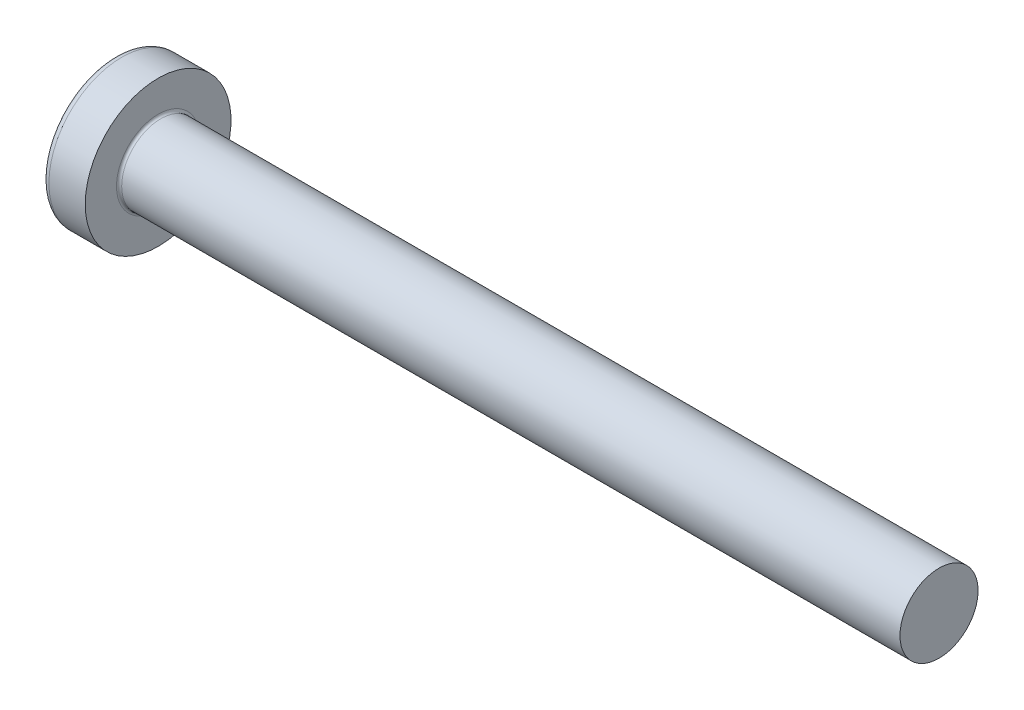
SolidWorks part; units mm, degrees
ref_plane "Plane1" through (0, 0, 0) normal (0, 0, 1) x (1, 0, 0)
ref_plane "Plane2" through (0, 0, 0) normal (0, 1, 0) x (1, 0, 0)
ref_plane "Plane3" through (0, 0, 0) normal (1, 0, 0) x (0, 0, -1)
sketch "BodySke" plane through (0, 0, 0) normal (0, 0, 1) x (1, 0, 0)
  line L0 (2.4, 1.5) -> (2.4, 2.8)
  line L1 (2.65, 6.35) -> (2.65, -3.175) construction
  line L2 (-25.4, 0) -> (127, 0) construction
  line L3 (32.4, 0) -> (0, 0)
  line L4 (2.4, 1.5) -> (32.4, 1.5)
  line L5 (32.4, 1.5) -> (32.4, 0)
  line L6 (1.0035, 2.8) -> (2.4, 2.8)
  line L8 (7.4, 6.35) -> (7.4, -3.175) construction
  arc A0 (0.7754, 2.6744) -> (0, 0) centre (5, 0) ccw
  arc A2 (0.7754, 2.6744) -> (1.0035, 2.8) centre (1.0035, 2.53) cw
  dimension "Thread_nom" = 25
revolve "Base-Revolve" add sketch "BodySke"
cosmetic thread "ThreadCosmetic" [suppressed]
fillet "Fillet1" radius 0.1 1 edges at (2.4, 0, 1.5)
sketch "Sketch3" plane through (0, 0, 0) normal (1, 0, 0) x (0, 0, -1)
  line L0 (0.37, -1.4) -> (-0.37, -1.4)
  line L1 (0.37, -1.4) -> (0.37, 1.4)
  line L2 (-0.37, 1.4) -> (0.37, 1.4)
  line L3 (-0.37, 1.4) -> (-0.37, -1.4)
ref_plane "Plane4" through (1.75, 0, 0) normal (1, 0, 0) x (0, 0, -1)
sketch "Sketch4" plane through (1.75, 0, 0) normal (1, 0, 0) x (0, 0, -1)
  line L0 (0.37, -0.5275) -> (-0.37, -0.5275)
  line L1 (0.37, -0.5275) -> (0.37, 0.5275)
  line L2 (-0.37, 0.5275) -> (0.37, 0.5275)
  line L3 (-0.37, 0.5275) -> (-0.37, -0.5275)
loft "Recess" cut profiles "Sketch3", "Sketch4"
pattern_circular "RecPat" count 2 every 90 about axis through (0, 0, 0) along (1, 0, 0) of "Recess"
sketch "RecCorSke" plane through (0, 0, 0) normal (0, 0, 1) x (1, 0, 0)
  line L0 (-3.175, 0) -> (15.875, 0) construction
  line L1 (-25.4, 0) -> (127, 0) construction
  line L2 (0, 0) -> (0, 0.6784)
  line L3 (0, 0.6784) -> (1.75, 0.556)
  line L4 (1.75, 0.556) -> (1.9307, 0)
  line L5 (1.9307, 0) -> (0, 0)
  dimension "Draft_angle" = 4
  dimension "Bottom_angle" = 18
revolve "RecessCore" cut sketch "RecCorSke" angle 360 about L0
sketch "ThdSchSke" plane through (0, 0, 0) normal (0, 0, 1) x (1, 0, 0)
  line L0 (7.4, -1.2195) -> (7.2036, -1.5)
  line L1 (7.4, -1.2195) -> (7.5964, -1.5)
  line L2 (7.5964, -1.5) -> (7.5964, -1.875)
  line L3 (-3.175, 0) -> (5.1513, 0) construction
  line L5 (7.5964, -1.875) -> (7.2036, -1.875)
  line L6 (7.2036, -1.875) -> (7.2036, -1.5)
  dimension "SideAngle" = 55
  dimension "VeeAngle" = 70
revolve "ThreadSchematic" [suppressed] cut sketch "ThdSchSke" angle 360 about L3
pattern_linear "ThdSchPat" [suppressed]
equation "\"D1@Sketch3\" = \"Cross_dia@Sketch3\" / 2"
equation "\"D2@Sketch3\" = \"Cross_width@Sketch3\" / 2"
equation "\"Depth@RecCorSke\" = \"Cross_depth@Plane4\""
equation "\"D1@Sketch4\" = \"Cross_width@Sketch3\""
equation "\"D2@Sketch4\" = \"Cross_dia@Sketch3\" - 2.0 * \"Cross_depth@Plane4\" * tan(26.5  * 0.017453292)"
equation "\"D3@Sketch4\" = \"D1@Sketch4\" / 2"
equation "\"D4@Sketch4\" = \"D2@Sketch4\" / 2"
equation "\"Thread_length@ThreadCosmetic\" = ((sgn( (\"Length@BodySke\" - \"Advance@BodySke\" * 2.0 ) - \"Thread_nom@BodySke\" )-1)*( (\"Length@BodySke\" - \"Advance@BodySke\" * 2.0 ) - \"Thread_nom@BodySke\" ))/-2+ \"Thread_nom@BodySke\""
equation "\"Thread_minor@ThdSchSke\" = \"Thread_minor@ThreadCosmetic\""
equation "\"Diameter@ThdSchSke\" = \"Diameter@BodySke\""
equation "\"Overcut@ThdSchSke\" = \"Diameter@BodySke\" * 1.25"
equation "\"Start@ThdSchSke\" = \"Head_ht@BodySke\" + \"Length@BodySke\" - \"Thread_length@ThreadCosmetic\"  '---Non-countersunk---"
equation "\"Num_threads@ThdSchPat\" = int( \"Thread_length@ThreadCosmetic\" / \"Advance@BodySke\" + 0.999 )  + 1"
equation "\"Advance@ThdSchPat\" = \"Thread_length@ThreadCosmetic\" /  (\"Num_threads@ThdSchPat\" - 1) 'relax it"
